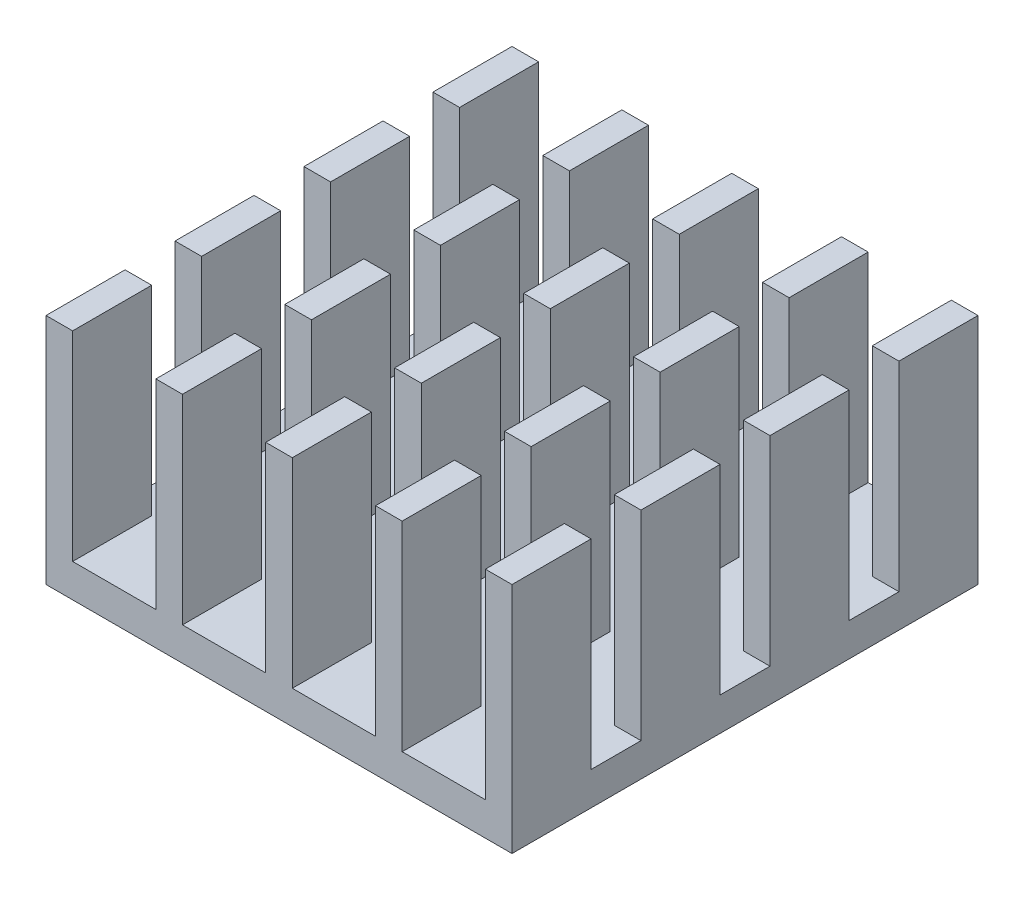
SolidWorks part; units mm, degrees
material "6061-T6 (SS)"
ref_plane "Front Plane" through (0, 0, 0) normal (0, 0, 1) x (1, 0, 0)
ref_plane "Top Plane" through (0, 0, 0) normal (0, 1, 0) x (1, 0, 0)
ref_plane "Right Plane" through (0, 0, 0) normal (1, 0, 0) x (0, 0, -1)
sketch "Sketch1" plane through (0, 0, 0) normal (0, 0, 1) x (1, 0, 0)
  line L0 (-7, 0) -> (7, 0)
  line L1 (-7, 0) -> (-7, 7)
  line L2 (-7, 7) -> (-6.2, 7)
  line L3 (-6.2, 7) -> (-6.2, 1)
  line L4 (-6.2, 1) -> (-3.7, 1)
  line L5 (-3.7, 1) -> (-3.7, 7)
  line L6 (-3.7, 7) -> (-2.9, 7)
  line L7 (-2.9, 7) -> (-2.9, 1)
  line L9 (2.9, 1) -> (2.9, 7)
  line L10 (2.9, 7) -> (3.7, 7)
  line L11 (3.7, 7) -> (3.7, 1)
  line L12 (3.7, 1) -> (6.2, 1)
  line L13 (6.2, 1) -> (6.2, 7)
  line L14 (6.2, 7) -> (7, 7)
  line L15 (7, 7) -> (7, 0)
  line L16 (-2.9, 1) -> (-0.4, 1)
  line L17 (-0.4, 1) -> (-0.4, 7)
  line L18 (-0.4, 7) -> (0.4, 7)
  line L19 (0.4, 7) -> (0.4, 1)
  line L20 (0.4, 1) -> (2.9, 1)
  point P20 (-0.8364, 1.3089)
  dimension "D1" = 14
  dimension "D2" = 0.8
  dimension "D3" = 1
  dimension "D4" = 7
extrude "Boss-Extrude1" add sketch "Sketch1" along normal blind 14
sketch "Sketch2" plane through (-7, 0, 0) normal (-1, 0, 0) x (0, 0, 1)
  line L0 (14, 7) -> (0, 7) construction
  line L1 (2.375, 7) -> (3.875, 7)
  line L2 (2.375, 7) -> (2.375, 1)
  line L3 (2.375, 1) -> (3.875, 1)
  line L4 (3.875, 7) -> (3.875, 1)
  line L5 (2.375, 1) -> (0, 1) construction
  line L6 (6.25, 7) -> (7.75, 7)
  line L7 (6.25, 7) -> (6.25, 1)
  line L8 (6.25, 1) -> (7.75, 1)
  line L9 (7.75, 7) -> (7.75, 1)
  line L10 (10.125, 7) -> (11.625, 7)
  line L11 (10.125, 7) -> (10.125, 1)
  line L12 (10.125, 1) -> (11.625, 1)
  line L13 (11.625, 7) -> (11.625, 1)
  line L14 (0, 7) -> (0, 0) construction
  line L15 (3.875, 1) -> (6.25, 1) construction
  line L16 (7.75, 1) -> (10.125, 1) construction
  line L17 (11.625, 1) -> (14, 1) construction
  line L18 (14, 7) -> (14, 0) construction
  line L19 (14, 1) -> (0, 1) construction
  point P20 (2.375, 1.8727)
  dimension "D1" = 1.5
extrude "Cut-Extrude1" cut sketch "Sketch2" against normal through all
